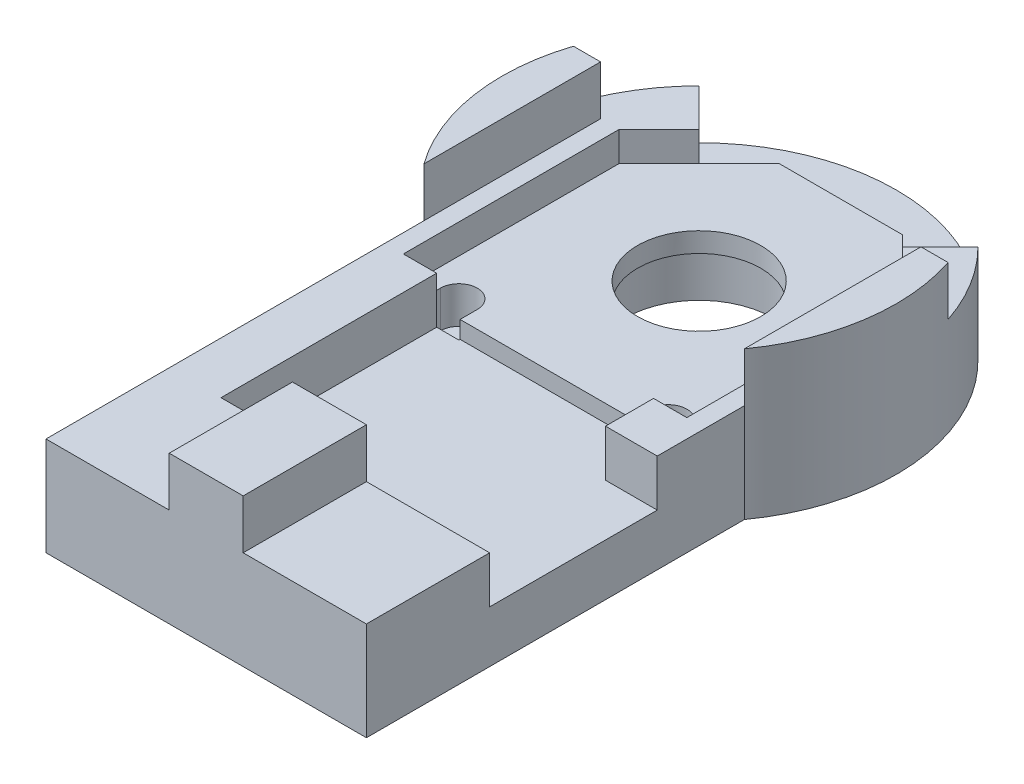
SolidWorks part; units mm, degrees
ref_plane "Front Plane" through (0, 0, 0) normal (0, 0, 1) x (1, 0, 0)
ref_plane "Top Plane" through (0, 0, 0) normal (0, 1, 0) x (1, 0, 0)
ref_plane "Right Plane" through (0, 0, 0) normal (1, 0, 0) x (0, 0, -1)
sketch "Sketch1" plane through (0, 0, 0) normal (0, 1, 0) x (1, 0, 0)
  line L0 (-1000.8836, -20) -> (48999.1164, -20) construction
  line L4 (6.5, -1010) -> (6.5, -4.6637) construction
  line L5 (6.5, -4.6637) -> (6.5, 4.6637) construction
  line L6 (-6.5, -1010) -> (-6.5, -4.6637) construction
  line L7 (6.5, -20) -> (6.5, -4.6637)
  line L8 (6.5, -20) -> (-6.5, -20)
  line L9 (-6.5, -20) -> (-6.5, -4.6637)
  line L10 (6.5, 4.6637) -> (6.5, 48990) construction
  line L11 (6.5, -4.6637) -> (6.5, 4.6637) construction
  line L12 (-6.5, -4.6637) -> (-6.5, 4.6637) construction
  line L13 (-6.5, -4.6637) -> (-6.5, 4.6637) construction
  line L14 (-6.5, 4.6637) -> (-6.5, 48990) construction
  arc A0 (6.5, 4.6637) -> (-6.5, 4.6637) centre (0, 0) ccw
  arc A1 (-8, 0) -> (-6.5, -4.6637) centre (0, 0) ccw
  arc A2 (-6.5, 4.6637) -> (-8, 0) centre (0, 0) ccw
  arc A3 (8, 0) -> (6.5, 4.6637) centre (0, 0) ccw
  arc A4 (-6.5, -4.6637) -> (6.5, -4.6637) centre (0, 0) ccw construction
  arc A5 (6.5, -4.6637) -> (8, 0) centre (0, 0) ccw
  dimension "D1" = 16
  dimension "D2" = 20
  dimension "D3" = 6.5
  dimension "D4" = 6.5
extrude "Boss-Extrude1" add sketch "Sketch1" along normal blind 4
sketch "Sketch2" plane through (0, 0, 0) normal (0, -1, 0) x (1, 0, 0)
  circle A0 centre (0, 0) radius 3
  dimension "D1" = 6
extrude "Cut-Extrude1" cut sketch "Sketch2" against normal blind 2
sketch "Sketch3" plane through (0, 2, 0) normal (0, -1, 0) x (1, 0, 0)
  circle A0 centre (0, 0) radius 1.5
  dimension "D1" = 3
extrude "Cut-Extrude2" cut sketch "Sketch3" against normal through all
sketch "Sketch5" plane through (0, 4, 0) normal (0, 1, 0) x (1, 0, 0)
  line L0 (-5.75, 0) -> (5.75, 0) construction
  line L1 (-5.75, -1000) -> (-5.75, -30) construction
  line L2 (5.75, -1000) -> (5.75, -30) construction
  line L3 (0, 0) -> (0, 5.75) construction
  line L4 (-1000, 5.75) -> (-0.75, 5.75) construction
  line L5 (2.5, 5.75) -> (0.75, 5.75)
  line L6 (-2.5, 5.75) -> (-5.75, 2.5)
  line L7 (-5.75, 2.5) -> (-5.75, -6.25)
  line L8 (2.5, 5.75) -> (5.75, 2.5)
  line L9 (5.75, 2.5) -> (5.75, -6.25)
  line L11 (-0.75, 5.75) -> (-0.75, 7.9648)
  line L12 (0.75, 5.75) -> (0.75, 7.9648)
  line L13 (-0.75, 5.75) -> (0, 5.75) construction
  line L14 (0.75, 5.75) -> (49000, 5.75) construction
  line L15 (0, 5.75) -> (-0.75, 5.75) construction
  line L16 (-0.75, 5.75) -> (-2.5, 5.75)
  line L17 (0.75, 5.75) -> (0, 5.75) construction
  line L18 (0, 5.75) -> (0.75, 5.75) construction
  line L20 (-5.75, -6.25) -> (-4.4, -6.25)
  line L21 (-5.5, -6.5) -> (5.5, -6.5) construction
  line L22 (-4.4, -6.25) -> (-4.4, -8.2)
  line L23 (-4.4, -24.811) -> (-4.4, -26.311) construction
  line L26 (-4.4, -6.25) -> (4.4, -6.25) construction
  line L27 (4.4, -6.25) -> (5.75, -6.25)
  line L28 (-2.9, -6.8941) -> (-2.9, -8.2) construction
  line L29 (-4.4, -8.2) -> (-5.66, -10)
  line L30 (6.5, -15) -> (6.5, -20.6628) construction
  line L31 (-754.0755, -8.2) -> (49245.9245, -8.2) construction
  line L32 (2.9, -8.2) -> (2.1, -8.2) construction
  line L33 (4.4, -8.2) -> (5.66, -10) construction
  line L34 (-4.4, -8.2) -> (-5.66, -10) construction
  line L36 (-4.4, -8.2) -> (-4.4, -24.811) construction
  line L40 (4.4, -13.8787) -> (4.4, -17.9429) construction
  line L41 (4.4, -8.2) -> (4.4, -13.8787) construction
  line L43 (-6.5, -4.6637) -> (-6.5, -20) construction
  line L44 (6.5, -20) -> (6.5, -4.6637) construction
  line L45 (6.5, -11.2) -> (6.5, -15)
  line L47 (-6.5, -15) -> (-6.5, -11.2)
  line L49 (-6.5, -15) -> (6.5, -15)
  line L51 (-1005.75, 2.5) -> (48994.25, 2.5) construction
  line L52 (-6.5, -20.6628) -> (-6.5, -15) construction
  line L53 (-5.75, -19.937) -> (-5.75, -15) construction
  line L55 (-998.9168, -10) -> (49001.0832, -10) construction
  line L56 (5.66, -10) -> (6.5, -10) construction
  line L57 (6.5, -20.6628) -> (8.4925, -22.5911) construction
  line L58 (-6.5, -20.6628) -> (-8.4521, -22.5519) construction
  line L59 (6.5, -20) -> (6.5, -4.6637) construction
  line L60 (-5.75, -30) -> (-5.75, -19.937) construction
  line L61 (-5.75, -15) -> (-5.75, 49000) construction
  line L62 (6.5, -10) -> (6.5, -11.2)
  line L63 (5.75, -10.1286) -> (6.5, -11.2) construction
  line L64 (4.4, -17.9429) -> (4.4, -30.2801) construction
  line L65 (5.75, -30) -> (5.75, -19.937) construction
  line L66 (5.75, -19.937) -> (5.75, 49000) construction
  line L67 (6.5, -20.6628) -> (6.5, -20) construction
  line L68 (5.66, -10) -> (5.75, -10.1286) construction
  line L69 (-5.66, -10) -> (-6.5, -10) construction
  line L70 (-6.5, -4.6637) -> (-6.5, -20) construction
  line L71 (-6.5, -10) -> (-6.5, -11.2)
  line L72 (-5.66, -10) -> (-5.75, -10.1286) construction
  line L73 (-5.75, -10.1286) -> (-6.5, -11.2)
  line L74 (4.4, -6.25) -> (4.4, -8.2)
  line L75 (-5.66, -10) -> (-6.5, -10)
  line L76 (4.4, -8.2) -> (6.5, -8.2)
  line L77 (6.5, -8.2) -> (6.5, -10)
  circle A0 centre (0, 0) radius 8 construction
  arc A2 (-0.75, 7.9648) -> (0.75, 7.9648) centre (0, 0) cw
  point P5 (0, 0)
  point P17 (0, 5.75)
  dimension "D1" = 5.75
  dimension "D2" = 0.75
  dimension "D3" = 0.75
  dimension "D4" = 11.5
  dimension "D5" = 0.25
  dimension "D6" = 1.5
  dimension "D8" = 3
  dimension "D9" = 3
  dimension "D10" = 2.5
  dimension "D11" = 10
  dimension "D12" = 15
  dimension "D13" = 2.1
extrude "Cut-Extrude4" cut sketch "Sketch5" against normal blind 1.2
sketch "Sketch6" plane through (0, 2.8, 0) normal (0, 1, 0) x (1, 0, 0)
  circle A0 centre (0, 0) radius 2.5
  dimension "D1" = 5
sketch "Sketch7" plane through (0, 2.8, 0) normal (0, 1, 0) x (1, 0, 0)
  line L0 (-5, -5.5) -> (-5, -6.25)
  line L1 (-3.5, -5.5) -> (-3.5, -6.25)
  line L2 (3.5, -5.5) -> (3.5, -6.25)
  line L3 (5, -5.5) -> (5, -6.25)
  line L4 (4.4, -6.25) -> (5.75, -6.25) construction
  line L5 (3.5, -6.25) -> (5, -6.25)
  line L6 (-5.75, -6.25) -> (-4.4, -6.25) construction
  line L7 (-5, -6.25) -> (-3.5, -6.25)
  arc A0 (-3.5, -5.5) -> (-5, -5.5) centre (-4.25, -5.5) ccw
  arc A1 (5, -5.5) -> (3.5, -5.5) centre (4.25, -5.5) ccw
  arc A5 (-5, -5.5) -> (-3.5, -5.5) centre (-4.25, -5.5) ccw construction
  arc A6 (3.5, -5.5) -> (5, -5.5) centre (4.25, -5.5) ccw construction
  dimension "D1" = 1.5
  dimension "D2" = 1.5
extrude "Cut-Extrude6" cut sketch "Sketch7" against normal blind 1.5
sketch "Sketch9" plane through (0, 2.8, 0) normal (0, 1, 0) x (1, 0, 0)
  line L0 (-6.5, -15) -> (6.5, -15)
  line L1 (6.5, -15) -> (6.5, -8.2)
  line L5 (-6.5, -10) -> (-6.5, -15)
  line L6 (-4.4, -8.2) -> (-4.4, -6.2)
  line L7 (-6.5, -15) -> (6.5, -15) construction
  line L8 (4.4, -8.2) -> (4.4, -6.2)
  line L10 (4.4, -6.2) -> (-4.4, -6.2)
  line L15 (6.5, -8.2) -> (4.4, -8.2)
  line L19 (-6.5, -10) -> (-6.5, -15) construction
  line L23 (-6.5, -10) -> (-6.5, -15) construction
  line L24 (-6.5, -10) -> (-5.66, -10)
  line L25 (-5.66, -10) -> (-4.4, -8.2)
  dimension "D1" = 2
extrude "Cut-Extrude7" cut sketch "Sketch9" against normal blind 0.7
sketch "Sketch11" plane through (0, 0, 20) normal (0, 0, 1) x (1, 0, 0)
  line L0 (-6.5, 4) -> (-6.5, 0) construction
  line L1 (-6.5, 4) -> (6.5, 4)
  line L2 (-6.5, 4) -> (-6.5, 0)
  line L3 (-6.5, 0) -> (6.5, 0)
  line L4 (6.5, 4) -> (6.5, 0)
  line L5 (-6.5, 4) -> (6.5, 4) construction
extrude "Cut-Extrude9" [suppressed] cut sketch "Sketch11" against normal up to vertex
sketch "Sketch14" plane through (0, 4, 0) normal (0, 1, 0) x (1, 0, 0)
  line L0 (6.5, -4.6637) -> (6.5, 2.5)
  line L1 (-6.5, -4.6637) -> (-6.5, 2.5)
  line L2 (-1005.75, 2.5) -> (48994.25, 2.5) construction
  line L3 (-6.5, 2.5) -> (-7.5993, 2.5)
  line L4 (6.5, 2.5) -> (7.5993, 2.5)
  line L5 (-6.5, 2.5) -> (-6.5, 4.6637) construction
  line L6 (6.5, 2.5) -> (6.5, 4.6637) construction
  arc A0 (6.5, -4.6637) -> (0.75, 7.9648) centre (0, 0) ccw construction
  arc A1 (-0.75, 7.9648) -> (-6.5, -4.6637) centre (0, 0) ccw construction
  arc A2 (6.5, -4.6637) -> (7.5993, 2.5) centre (0, 0) ccw
  arc A3 (-6.5, -4.6637) -> (-7.5993, 2.5) centre (0, 0) cw
  arc A4 (-7.5993, 2.5) -> (-6.5, 4.6637) centre (0, 0) cw construction
  arc A5 (7.5993, 2.5) -> (6.5, 4.6637) centre (0, 0) ccw construction
  dimension "D1" = 8
  dimension "D2" = 8
extrude "Boss-Extrude3" add sketch "Sketch14" along normal blind 2
sketch "Sketch15" plane through (0, 4, 0) normal (0, 1, 0) x (1, 0, 0)
  line L0 (2.5, 5.75) -> (-2.5, 5.75)
  line L3 (0, 0) -> (35355.3391, 35355.3391) construction
  line L4 (5.75, 2.5) -> (2.5, 5.75) construction
  line L5 (0, 0) -> (-35355.3391, 35355.3391) construction
  line L6 (-2.5, 5.75) -> (-5.75, 2.5) construction
  line L7 (2.5, 5.75) -> (4.125, 4.125)
  line L8 (4.125, 4.125) -> (5.6569, 5.6569)
  line L9 (-2.5, 5.75) -> (-4.125, 4.125)
  line L10 (-4.125, 4.125) -> (-5.6569, 5.6569)
  arc A0 (-0.75, 7.9648) -> (-7.5993, 2.5) centre (0, 0) ccw construction
  arc A1 (7.5993, 2.5) -> (0.75, 7.9648) centre (0, 0) ccw construction
  arc A2 (5.6569, 5.6569) -> (-5.6569, 5.6569) centre (0, 0) ccw
  point P18 (4.125, 4.125)
  point P23 (-4.125, 4.125)
extrude "Cut-Extrude12" cut sketch "Sketch15" against normal blind 2
extrude "Cut-Extrude13" cut sketch "Sketch6" against normal through all
sketch "Sketch16" plane through (0, 4, 0) normal (0, 1, 0) x (1, 0, 0)
  line L0 (0, -20) -> (0, -15) construction
  line L1 (-6.5, -20) -> (6.5, -20) construction
  line L2 (-6.5, -15) -> (6.5, -15) construction
  line L3 (-1.5, -15) -> (1.5, -15)
  line L4 (-1.5, -15) -> (-1.5, -20)
  line L5 (1.5, -15) -> (1.5, -20)
  line L6 (-1.5, -20) -> (1.5, -20)
  dimension "D1" = 1.5
  dimension "D2" = 1.5
  dimension "D3" = 5
extrude "Boss-Extrude4" add sketch "Sketch16" along normal blind 2
sketch "Sketch18" plane through (0, 2.1, 0) normal (0, 1, 0) x (1, 0, 0)
  line L0 (-4.4, -8.2) -> (-5.66, -10)
  line L1 (-5.66, -10) -> (-6.5, -10)
  line L2 (-6.5, -10) -> (-6.5, -15)
  line L3 (-6.5, -15) -> (-4.4, -15)
  line L4 (-6.5, -15) -> (6.5, -15) construction
  line L5 (-4.4, -8.2) -> (-4.4, -15)
extrude "Boss-Extrude6" add sketch "Sketch18" along normal up to surface (1.9 mm away) up to face at (-5.7297, 4, 2.5425)
